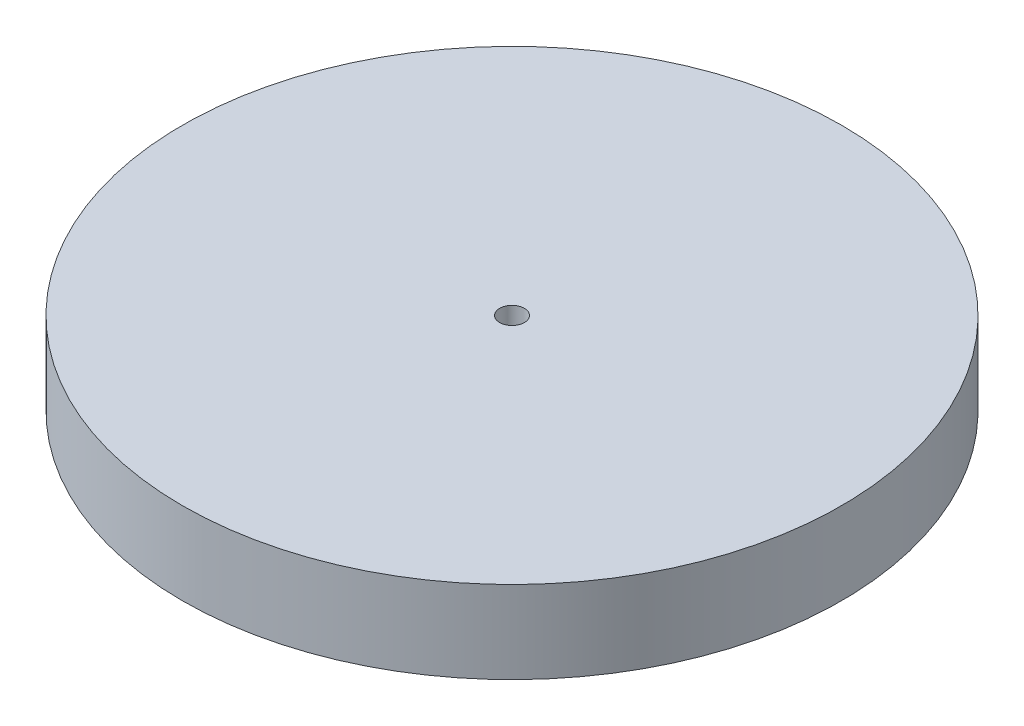
SolidWorks part; units mm, degrees
ref_plane "前基準面" through (0, 0, 0) normal (0, 0, 1) x (1, 0, 0)
ref_plane "上基準面" through (0, 0, 0) normal (0, 1, 0) x (1, 0, 0)
ref_plane "右基準面" through (0, 0, 0) normal (1, 0, 0) x (0, 0, -1)
sketch "草圖1" plane through (0, 0, 0) normal (0, 1, 0) x (1, 0, 0)
  circle A0 centre (0, 0) radius 40
  circle A1 centre (0, 0) radius 1.5
  dimension "D1" = 3
  dimension "D2" = 80
extrude "填料-伸長1" add sketch "草圖1" along normal blind 10
